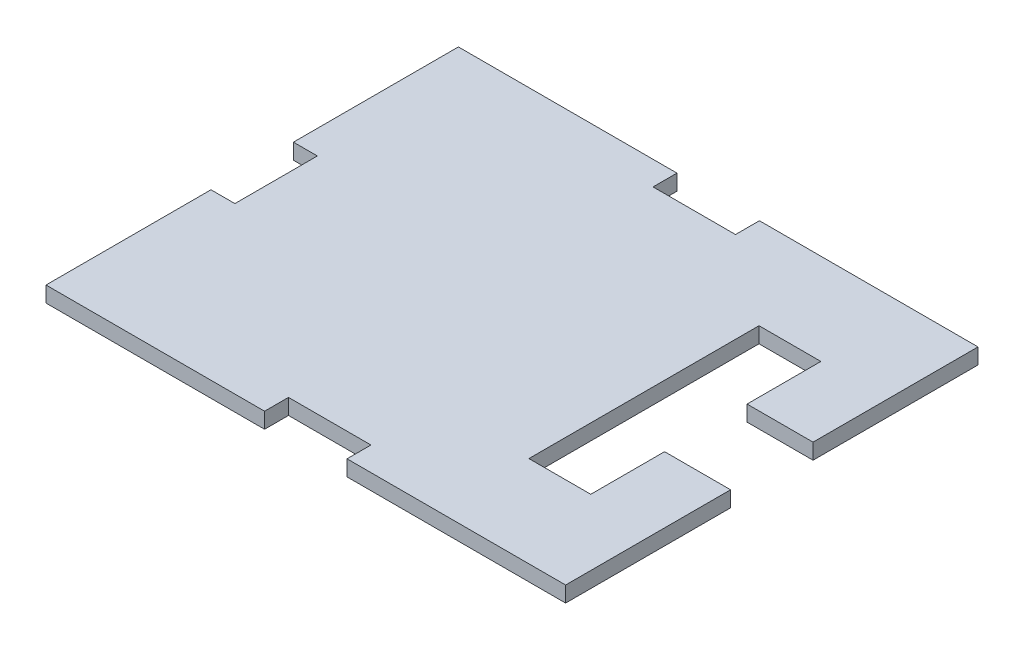
SolidWorks part; units mm, degrees
ref_plane "Front Plane" through (0, 0, 0) normal (0, 0, 1) x (1, 0, 0)
ref_plane "Top Plane" through (0, 0, 0) normal (0, 1, 0) x (1, 0, 0)
ref_plane "Right Plane" through (0, 0, 0) normal (1, 0, 0) x (0, 0, -1)
sketch "Sketch1" plane through (0, 0, 0) normal (0, 1, 0) x (1, 0, 0)
  line L0 (-80.01, 0) -> (80.01, 0) construction
  line L1 (-80.01, 63.5) -> (-12.7, 63.5)
  line L2 (-80.01, 63.5) -> (-80.01, 12.7)
  line L3 (-80.01, -63.5) -> (-12.7, -63.5)
  line L4 (80.01, 63.5) -> (80.01, 12.7)
  line L5 (-80.01, 63.5) -> (80.01, -63.5) construction
  line L6 (-80.01, -63.5) -> (80.01, 63.5) construction
  line L8 (-12.7, 63.5) -> (-12.7, 56.134)
  line L9 (-12.7, 56.134) -> (12.7, 56.134)
  line L10 (12.7, 63.5) -> (12.7, 56.134)
  line L11 (0, -63.5) -> (0, 105.7872) construction
  line L12 (-12.7, -63.5) -> (-12.7, -56.134)
  line L13 (12.7, -63.5) -> (12.7, -56.134)
  line L14 (-12.7, -56.134) -> (12.7, -56.134)
  line L15 (-80.01, 12.7) -> (-72.644, 12.7)
  line L16 (80.01, -12.7) -> (72.644, -12.7)
  line L18 (80.01, 12.7) -> (72.644, 12.7)
  line L19 (72.644, -12.7) -> (72.644, 12.7)
  line L20 (-80.01, -12.7) -> (-72.644, -12.7)
  line L21 (-72.644, -12.7) -> (-72.644, 12.7)
  line L22 (-80.01, -12.7) -> (-80.01, -63.5)
  line L23 (12.7, 63.5) -> (80.01, 63.5)
  line L24 (12.7, -63.5) -> (80.01, -63.5)
  line L25 (80.01, -12.7) -> (80.01, -63.5)
  point P0 (0, 0)
  dimension "D1" = 160.02
  dimension "D2" = 127
  dimension "D3" = 7.366
  dimension "D4" = 25.4
  dimension "D5" = 67.31
  dimension "D6" = 50.8
  dimension "D7" = 25.4
  dimension "D8" = 7.366
extrude "Boss-Extrude1" add sketch "Sketch1" along normal blind 4.826
sketch "Sketch3" plane through (0, 4.826, 0) normal (0, 1, 0) x (1, 0, 0)
  line L1 (59.69, -35.433) -> (40.64, -35.433)
  line L2 (59.69, -35.433) -> (59.69, -12.7)
  line L3 (59.69, 35.433) -> (40.64, 35.433)
  line L4 (40.64, -35.433) -> (40.64, 35.433)
  line L5 (59.69, -35.433) -> (40.64, 35.433) construction
  line L6 (59.69, 35.433) -> (40.64, -35.433) construction
  line L8 (-80.01, -12.7) -> (-80.01, -63.5) construction
  line L9 (72.644, 12.7) -> (80.01, 12.7) construction
  line L10 (72.644, -12.7) -> (59.69, -12.7)
  line L11 (72.644, -12.7) -> (72.644, 12.7)
  line L12 (72.644, 12.7) -> (59.69, 12.7)
  line L14 (59.69, 12.7) -> (59.69, 35.433)
  point P0 (50.165, 0)
  dimension "D1" = 70.866
  dimension "D2" = 120.65
  dimension "D3" = 19.05
extrude "Cut-Extrude1" cut sketch "Sketch3" against normal blind 4.826
